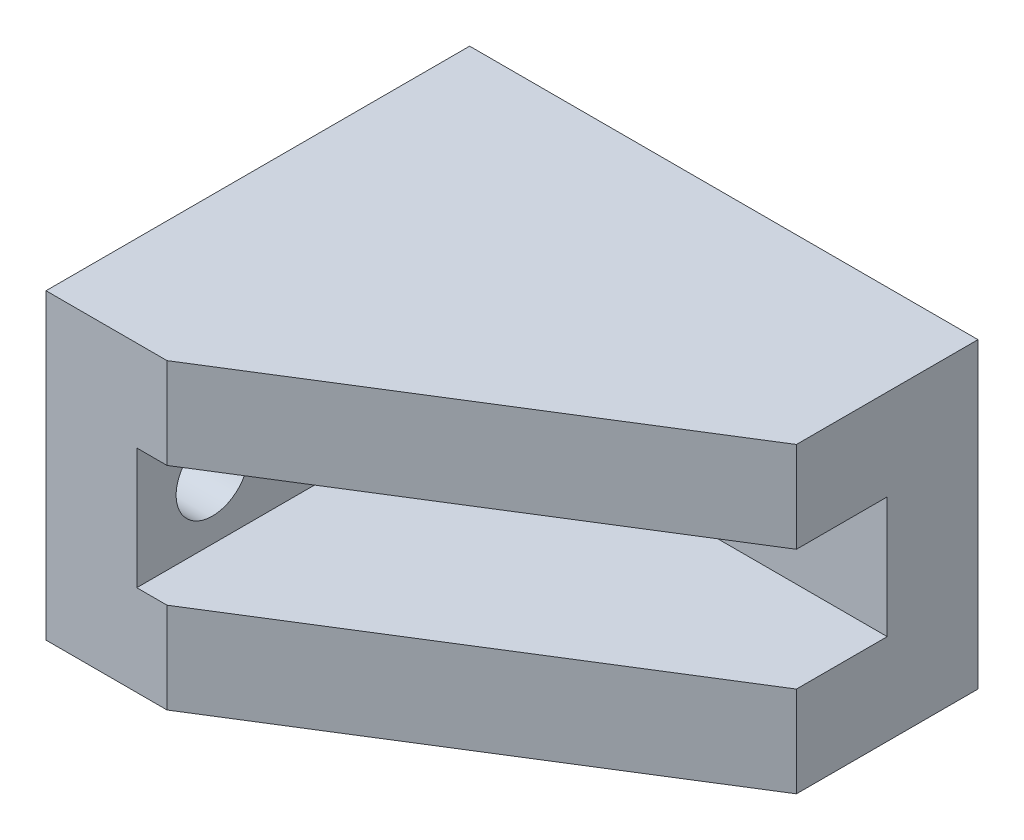
SolidWorks part; units mm, degrees
ref_plane "Front Plane" through (0, 0, 0) normal (0, 0, 1) x (1, 0, 0)
ref_plane "Top Plane" through (0, 0, 0) normal (0, 1, 0) x (1, 0, 0)
ref_plane "Right Plane" through (0, 0, 0) normal (1, 0, 0) x (0, 0, -1)
sketch "Sketch2" plane through (0, 0, 0) normal (0, 1, 0) x (1, 0, 0)
  line L0 (10, -35) -> (42, -15)
  line L1 (0, 0) -> (42, 0)
  line L2 (0, 0) -> (0, -35)
  line L3 (0, -35) -> (10, -35)
  line L4 (42, 0) -> (42, -15)
  dimension "15" = 15
  dimension "D2" = 10
  dimension "D3" = 42
  dimension "D4" = 35
extrude "Boss-Extrude1" add sketch "Sketch2" along normal blind 25
shell "Shell1" thickness 7.5
sketch "Sketch3" plane through (7.5, 0, 0) normal (1, 0, 0) x (0, 0, -1)
  line L0 (-35, 12.5) -> (-7.5, 12.5) construction
  line L1 (-35, 17.5) -> (-35, 7.5) construction
  line L2 (-7.5, 17.5) -> (-7.5, 7.5) construction
  line L3 (-21.25, 17.5) -> (-21.25, 7.5) construction
  line L4 (-7.5, 17.5) -> (-35, 17.5) construction
  line L5 (-7.5, 7.5) -> (-35, 7.5) construction
  circle A0 centre (-28.75, 12.5) radius 3
  circle A1 centre (-13.75, 12.5) radius 3
  dimension "D2" = 6
  dimension "D1" = 15
extrude "Cut-Extrude1" cut sketch "Sketch3" against normal blind 30
ref_plane "Plane1" through (0, 0, 0) normal (-0.7071, 0, 0.7071) x (0.7071, 0, 0.7071)
sketch "Sketch4" plane through (0, 0, 7.5) normal (0, 0, 1) x (1, 0, 0)
  line L0 (42, 12.5) -> (7.5, 12.5) construction
  line L1 (42, 17.5) -> (42, 7.5) construction
  line L2 (7.5, 17.5) -> (7.5, 7.5) construction
  line L3 (24.75, 17.5) -> (24.75, 7.5) construction
  line L7 (42, 17.5) -> (7.5, 17.5) construction
  line L10 (42, 7.5) -> (7.5, 7.5) construction
  circle A0 centre (17.25, 12.5) radius 2.5
  circle A1 centre (32.25, 12.5) radius 2.5
  dimension "D1" = 15
  dimension "D2" = 5
extrude "Cut-Extrude2" cut sketch "Sketch4" against normal blind 10
fillet "Fillet1" [suppressed] radius 3
sketch "Sketch6" plane through (0, 0, 0) normal (-1, 0, 0) x (0, 0, 1)
  line L4 (0, 0) -> (35, 0)
  line L5 (35, 0) -> (35, 25)
  line L6 (35, 25) -> (0, 25)
  line L7 (0, 25) -> (0, 0)
  line L8 (0, 0) -> (35, 0)
  line L9 (35, 0) -> (35, 25)
  line L10 (35, 25) -> (0, 25)
  line L11 (0, 25) -> (0, 0)
  circle A0 centre (28.75, 12.5) radius 3 construction
  circle A1 centre (13.75, 12.5) radius 3 construction
  circle A2 centre (28.75, 12.5) radius 3
  circle A3 centre (13.75, 12.5) radius 3
  dimension "D1" = 0
extrude "Boss-Extrude2" [suppressed] add sketch "Sketch6" along normal blind 2
